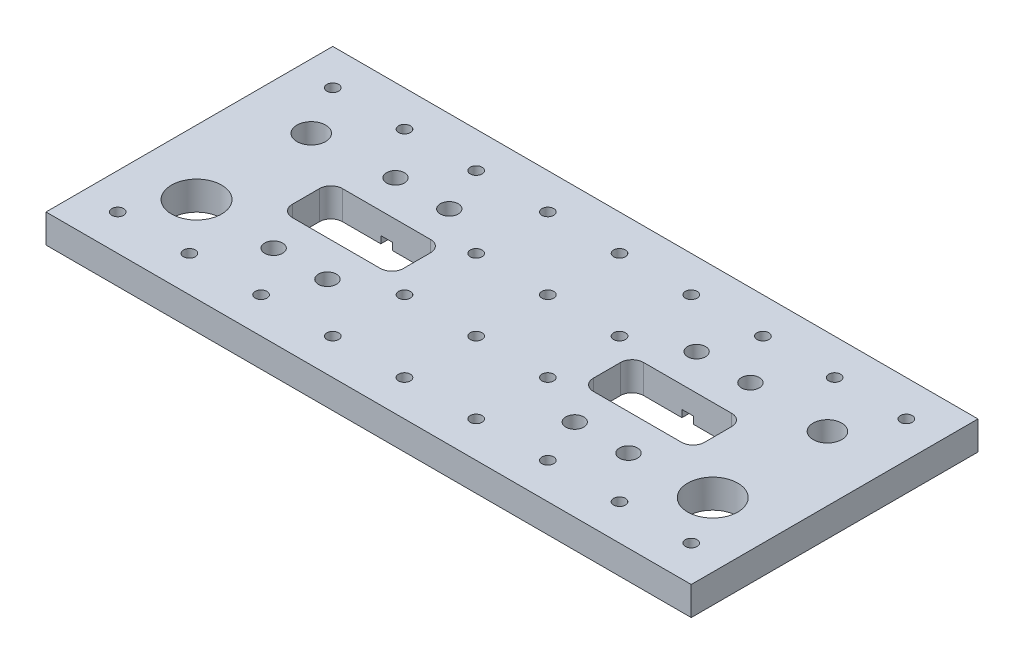
SolidWorks part; units mm, degrees
material "Plain Carbon Steel"
ref_plane "Front Plane" through (0, 0, 0) normal (0, 0, 1) x (1, 0, 0)
ref_plane "Top Plane" through (0, 0, 0) normal (0, 1, 0) x (1, 0, 0)
ref_plane "Right Plane" through (0, 0, 0) normal (1, 0, 0) x (0, 0, -1)
sketch "Sketch1" plane through (0, 0, 0) normal (0, 1, 0) x (1, 0, 0)
  line L1 (0, 0) -> (180, 0)
  line L2 (0, 0) -> (0, -80)
  line L3 (0, -80) -> (180, -80)
  line L4 (180, 0) -> (180, -80)
  dimension "D1" = 80
  dimension "D2" = 180
extrude "Boss-Extrude1" add sketch "Sketch1" along normal blind 8
sketch "Sketch2" plane through (0, 8, 0) normal (0, 1, 0) x (1, 0, 0)
  line L0 (0, 0) -> (0, -80) construction
  line L1 (180, 0) -> (0, 0) construction
  line L2 (90, 0) -> (90, -80) construction
  line L3 (0, -80) -> (180, -80) construction
  line L4 (0, -40) -> (180, -40) construction
  line L5 (180, -80) -> (180, 0) construction
  line L6 (116.5, -33) -> (116.5, -47)
  line L7 (32.5, -33) -> (63.5, -33)
  line L8 (32.5, -33) -> (32.5, -47)
  line L9 (32.5, -47) -> (63.5, -47)
  line L10 (63.5, -33) -> (63.5, -47)
  line L11 (147.5, -47) -> (116.5, -47)
  line L12 (147.5, -33) -> (147.5, -47)
  line L13 (147.5, -33) -> (116.5, -33)
  line L14 (0, -36) -> (180, -36) construction
  line L15 (0, -44) -> (180, -44) construction
  line L16 (48, -33) -> (48, -47) construction
  line L17 (0, -80) -> (180, -80) construction
  circle A0 centre (18, -24) radius 4
  circle A1 centre (162, -24) radius 4
  circle A2 centre (18, -56) radius 7
  circle A3 centre (162, -56) radius 7
  circle A4 centre (18, -24) radius 12 construction
  circle A5 centre (162, -24) radius 12 construction
  circle A6 centre (18, -56) radius 12 construction
  circle A7 centre (162, -56) radius 12 construction
  point P20 (32.5, -40)
  dimension "D3" = 8
  dimension "D6" = 14
  dimension "D11" = 24
  dimension "D12" = 24
  dimension "D1" = 18
  dimension "D2" = 24
  dimension "D4" = 24
  dimension "D5" = 18
  dimension "D7" = 31
  dimension "D8" = 14
  dimension "D9" = 42
  dimension "D10" = 4
extrude "Cut-Extrude1" cut sketch "Sketch2" against normal blind 30
fillet "Fillet1" radius 3.2 8 edges at (147.5, 4, 33) (147.5, 4, 47) (116.5, 4, 47) (116.5, 4, 33) (63.5, 4, 47) (63.5, 4, 33) (32.5, 4, 47) (32.5, 4, 33)
sketch "Sketch3" plane through (0, 0, 0) normal (0, -1, 0) x (1, 0, 0)
  line L0 (48, 47) -> (48, 70.8326) construction
  line L1 (35.7, 47) -> (60.3, 47) construction
  line L2 (46.4, 33) -> (49.6, 33)
  line L3 (46.4, 67) -> (49.6, 67)
  line L4 (46.4, 67) -> (46.4, 47)
  line L5 (46.4, 47) -> (49.6, 47)
  line L6 (32.5, 40) -> (63.5, 40) construction
  line L7 (32.5, 36.2) -> (32.5, 43.8) construction
  line L8 (63.5, 43.8) -> (63.5, 36.2) construction
  line L9 (63.5, 40) -> (147.5, 40) construction
  line L10 (147.5, 43.8) -> (147.5, 36.2) construction
  line L11 (49.6, 67) -> (49.6, 47)
  line L12 (49.6, 13) -> (49.6, 33)
  line L13 (46.4, 13) -> (49.6, 13)
  line L14 (46.4, 13) -> (46.4, 33)
  line L15 (133.6, 13) -> (130.4, 13)
  line L16 (133.6, 13) -> (133.6, 33)
  line L17 (133.6, 33) -> (130.4, 33)
  line L18 (130.4, 13) -> (130.4, 33)
  line L19 (90, 80) -> (90, 0) construction
  line L20 (0, 80) -> (180, 80) construction
  line L21 (180, 0) -> (0, 0) construction
  line L22 (133.6, 47) -> (130.4, 47)
  line L23 (133.6, 67) -> (133.6, 47)
  line L24 (133.6, 67) -> (130.4, 67)
  line L25 (130.4, 67) -> (130.4, 47)
  point P8 (48, 67)
  dimension "D1" = 3.2
  dimension "D2" = 20
sketch "Sketch5" plane through (0, 8, 0) normal (0, 1, 0) x (1, 0, 0)
  line L0 (0, -10) -> (180, -10) construction
  line L1 (0, 0) -> (0, -80) construction
  line L2 (180, -80) -> (180, 0) construction
  line L4 (180, 0) -> (0, 0) construction
  line L5 (90, 0) -> (90, -80) construction
  line L6 (0, -80) -> (180, -80) construction
  line L7 (0, -40) -> (180, -40) construction
  line L9 (100, -10) -> (100, -64.5161) construction
  line L10 (80, -10) -> (80, -64.5161) construction
  circle A0 centre (90, -10) radius 1.65
  circle A1 centre (70, -10) radius 1.65
  circle A2 centre (50, -10) radius 1.65
  circle A3 centre (30, -10) radius 1.65
  circle A4 centre (10, -10) radius 1.65
  circle A5 centre (170, -10) radius 1.65
  circle A6 centre (150, -10) radius 1.65
  circle A7 centre (130, -10) radius 1.65
  circle A8 centre (110, -10) radius 1.65
  circle A9 centre (170, -70) radius 1.65
  circle A10 centre (150, -70) radius 1.65
  circle A11 centre (130, -70) radius 1.65
  circle A12 centre (110, -70) radius 1.65
  circle A13 centre (90, -70) radius 1.65
  circle A14 centre (70, -70) radius 1.65
  circle A15 centre (50, -70) radius 1.65
  circle A16 centre (30, -70) radius 1.65
  circle A17 centre (10, -70) radius 1.65
  circle A18 centre (90, -30) radius 1.65
  circle A19 centre (90, -50) radius 1.65
  circle A20 centre (70, -50) radius 1.65
  circle A21 centre (70, -30) radius 1.65
  circle A22 centre (110, -50) radius 1.65
  circle A23 centre (110, -30) radius 1.65
  dimension "D2" = 3.3
  dimension "D4" = 3.3
  dimension "D5" = 3.3
  dimension "D6" = 3.3
  dimension "D10" = 3.3
  dimension "D11" = 3.3
  dimension "D12" = 20
  dimension "D13" = 10
  dimension "D14" = 10
  dimension "D1" = 10
  dimension "D3" = 20
  dimension "D7" = 20
  dimension "D8" = 20
  dimension "D9" = 20
extrude "Cut-Extrude4" cut sketch "Sketch5" against normal blind 8
extrude "Cut-Extrude5" cut sketch "Sketch3" against normal blind 2
sketch "Sketch7" plane through (0, 0, 0) normal (0, -1, 0) x (1, 0, 0)
  line L0 (46.4, 57) -> (32.5, 57) construction
  line L1 (48, 67) -> (48, 47) construction
  line L4 (46.4, 67) -> (46.4, 47) construction
  line L5 (49.6, 67) -> (46.4, 67) construction
  line L7 (32.5, 40) -> (63.5, 40) construction
  line L8 (32.5, 36.2) -> (32.5, 43.8) construction
  line L9 (63.5, 43.8) -> (63.5, 36.2) construction
  line L10 (90, 80) -> (90, 0) construction
  line L11 (0, 80) -> (180, 80) construction
  line L12 (180, 0) -> (0, 0) construction
  line L13 (46.4, 47) -> (49.6, 47) construction
  circle A0 centre (40.5, 57) radius 2.5
  circle A1 centre (55.5, 57) radius 2.5
  circle A2 centre (55.5, 23) radius 2.5
  circle A3 centre (40.5, 23) radius 2.5
  circle A4 centre (124.5, 23) radius 2.5
  circle A5 centre (139.5, 23) radius 2.5
  circle A6 centre (124.5, 57) radius 2.5
  circle A7 centre (139.5, 57) radius 2.5
  dimension "D1" = 5
extrude "Cut-Extrude6" cut sketch "Sketch7" against normal through all
equation "\"D1@Sketch1\"=80"
equation "\"D7@Sketch2\"=24+2*3.5"
equation "\"D10@Sketch2\"=8/2"
